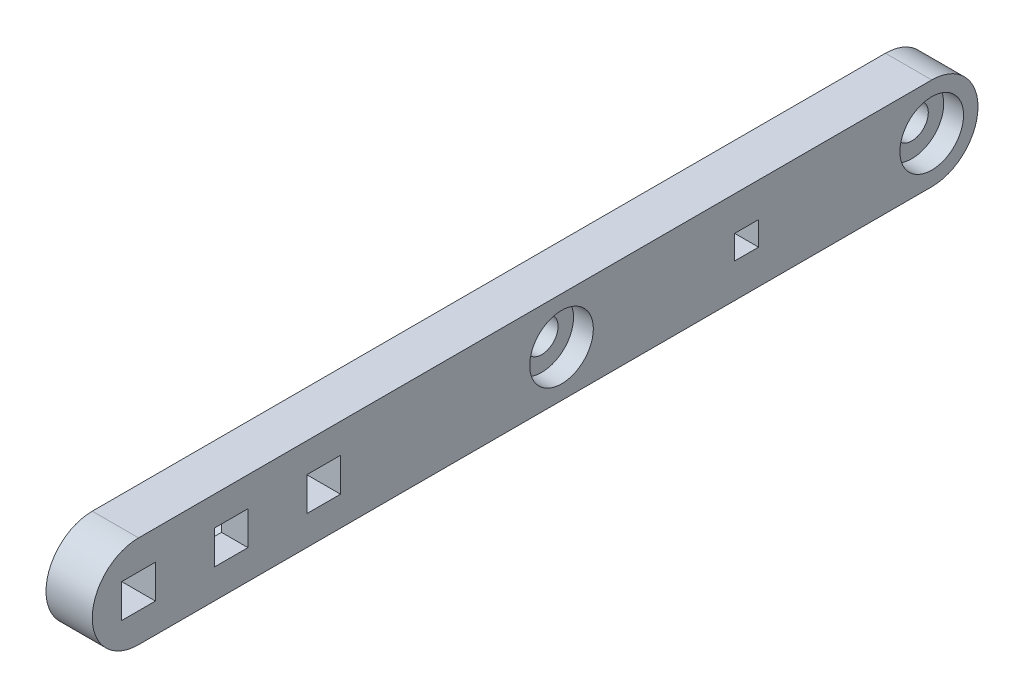
SolidWorks part; units mm, degrees
material "ABS"
ref_plane "Front Plane" through (0, 0, 0) normal (0, 0, 1) x (1, 0, 0)
ref_plane "Top Plane" through (0, 0, 0) normal (0, 1, 0) x (1, 0, 0)
ref_plane "Right Plane" through (0, 0, 0) normal (1, 0, 0) x (0, 0, -1)
sketch "Sketch1" plane through (0, 0, 0) normal (1, 0, 0) x (0, 0, -1)
  line L0 (-73.0504, -2.3114) -> (-68.4276, -2.3114)
  line L1 (-83.439, 6.35) -> (0, 6.35)
  line L2 (-83.439, 6.35) -> (-83.439, -6.35)
  line L3 (-83.439, -6.35) -> (0, -6.35)
  line L4 (0, 6.35) -> (0, -6.35)
  line L5 (-1.6375, 1.6375) -> (1.6375, 1.6375)
  line L6 (-1.6375, 1.6375) -> (-1.6375, -1.6375)
  line L7 (-1.6375, -1.6375) -> (1.6375, -1.6375)
  line L8 (1.6375, 1.6375) -> (1.6375, -1.6375)
  line L9 (-1.6375, 1.6375) -> (1.6375, -1.6375) construction
  line L10 (-1.6375, -1.6375) -> (1.6375, 1.6375) construction
  line L11 (-85.7504, 2.3114) -> (-81.1276, 2.3114)
  line L12 (-85.7504, 2.3114) -> (-85.7504, -2.3114)
  line L13 (-85.7504, -2.3114) -> (-81.1276, -2.3114)
  line L14 (-81.1276, 2.3114) -> (-81.1276, -2.3114)
  line L15 (-85.7504, 2.3114) -> (-81.1276, -2.3114) construction
  line L16 (-85.7504, -2.3114) -> (-81.1276, 2.3114) construction
  line L17 (-68.4276, 2.3114) -> (-68.4276, -2.3114)
  line L18 (-73.0504, 2.3114) -> (-68.4276, 2.3114)
  line L19 (-73.0504, 2.3114) -> (-73.0504, -2.3114)
  line L20 (-60.3504, -2.3114) -> (-55.7276, -2.3114)
  line L21 (-55.7276, 2.3114) -> (-55.7276, -2.3114)
  line L22 (-60.3504, 2.3114) -> (-55.7276, 2.3114)
  line L23 (-60.3504, 2.3114) -> (-60.3504, -2.3114)
  line L25 (0, -6.35) -> (25.4, -6.35)
  line L26 (0, -6.35) -> (0, 6.35)
  line L27 (0, 6.35) -> (25.4, 6.35)
  line L28 (25.4, -6.35) -> (25.4, 6.35)
  circle A0 centre (0, 0) radius 38.1 construction
  circle A2 centre (-83.439, 0) radius 6.35
  circle A3 centre (0, 0) radius 6.35 construction
  circle A4 centre (25.4, 0) radius 6.35
  point P7 (0, 0)
  point P9 (-63.5, 0)
  point P32 (-25.4, 0)
  point P33 (25.4, 0)
  dimension "D1" = 76.2
  dimension "D4" = 3
  dimension "D5" = 3.275
  dimension "D2" = 12.7
  dimension "D3" = 83.439
  dimension "D6" = 4.6228
  dimension "D7" = 12.7
  dimension "D8" = 63.5
  dimension "D9" = 25.4
  dimension "D10" = 50.8
extrude "Boss-Extrude1" add sketch "Sketch1" along normal blind 6.35
sketch "Sketch5" plane through (6.35, 0, 0) normal (1, 0, 0) x (0, 0, -1)
  point P0 (-63.5, 0)
  point P1 (-25.4, 0)
  point P3 (25.4, 0)
hole_wizard "CBORE for #8 Button Head Cap Screw1" positions "3DSketch7" profile "Sketch7" counterbore size "#8" standard "ANSI Inch" end condition through all
sketch3d "3DSketch7"
  point P0 (6.35, 0, 25.4)
  point P3 (6.35, 0, -25.4)
sketch "Sketch7" plane through (6.35, 0, 25.4) normal (0, 1, 0) x (0, 0, -1)
  line L0 (0, 0) -> (0, 6.35)
  line L1 (0, 6.35) -> (2.2479, 6.35)
  line L3 (2.2479, 6.35) -> (2.2479, 2.7178)
  line L4 (2.2479, 2.7178) -> (4.3663, 2.7178)
  line L5 (4.3663, 2.7178) -> (4.3663, 0)
  line L7 (4.3663, 0) -> (0, 0)
  line L11 (0, -6.35) -> (0, 107.95) construction
  dimension "Thru Hole Dia." = 4.4958
  dimension "Thru Hole Depth" = 6.35
  dimension "C'Bore Dia." = 8.7325
  dimension "C'Bore Depth" = 2.7178
sketch "Sketch8" plane through (0, 0, 0) normal (-1, 0, 0) x (0, 0, 1)
  line L0 (73.0504, 2.3114) -> (68.4276, 2.3114) construction
  line L1 (73.0504, 2.3114) -> (73.0504, -2.3114) construction
  point P0 (70.739, 0)
  point P1 (0, 0)
  point P4 (70.739, 2.3114)
  point P7 (73.0504, 0)
hole_wizard "CBORE for #8 Button Head Cap Screw2" positions "3DSketch8" profile "Sketch9" counterbore size "#8" standard "ANSI Inch" end condition through all
sketch3d "3DSketch8"
  point P0 (0, 0, 70.739)
sketch "Sketch9" plane through (0, 0, 70.739) normal (0, 1, 0) x (0, 0, 1)
  line L0 (0, 0) -> (0, 6.35)
  line L1 (0, 6.35) -> (2.2479, 6.35)
  line L3 (2.2479, 6.35) -> (2.2479, 2.7178)
  line L4 (2.2479, 2.7178) -> (4.3663, 2.7178)
  line L5 (4.3663, 2.7178) -> (4.3663, 0)
  line L7 (4.3663, 0) -> (0, 0)
  line L11 (0, -6.35) -> (0, 107.95) construction
  dimension "Thru Hole Dia." = 4.4958
  dimension "Thru Hole Depth" = 6.35
  dimension "C'Bore Dia." = 8.7325
  dimension "C'Bore Depth" = 2.7178
